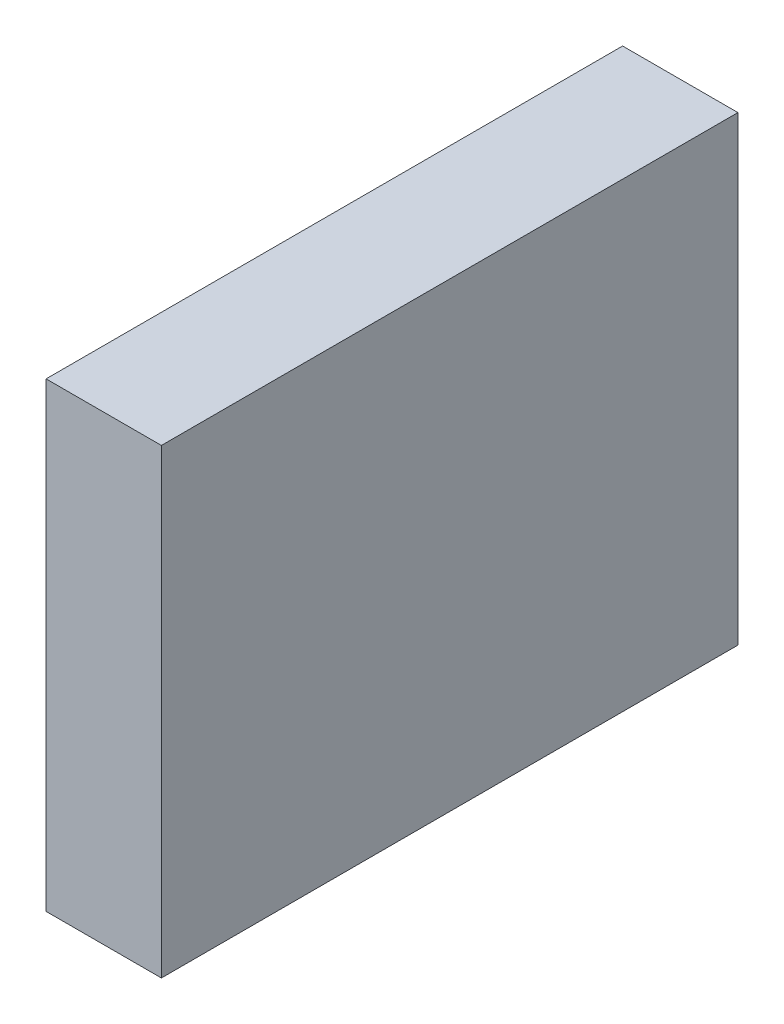
SolidWorks part; units mm, degrees
ref_plane "Front Plane" through (0, 0, 0) normal (0, 0, 1) x (1, 0, 0)
ref_plane "Top Plane" through (0, 0, 0) normal (0, 1, 0) x (1, 0, 0)
ref_plane "Right Plane" through (0, 0, 0) normal (1, 0, 0) x (0, 0, -1)
sketch "Sketch1" plane through (0, 0, 0) normal (0, 1, 0) x (1, 0, 0)
  line L1 (5, 25) -> (-5, 25)
  line L2 (5, 25) -> (5, -25)
  line L3 (5, -25) -> (-5, -25)
  line L4 (-5, 25) -> (-5, -25)
  line L5 (5, 25) -> (-5, -25) construction
  line L6 (5, -25) -> (-5, 25) construction
  point P0 (0, 0)
  dimension "D1" = 50
  dimension "D2" = 10
extrude "Boss-Extrude1" add sketch "Sketch1" along normal blind 40
